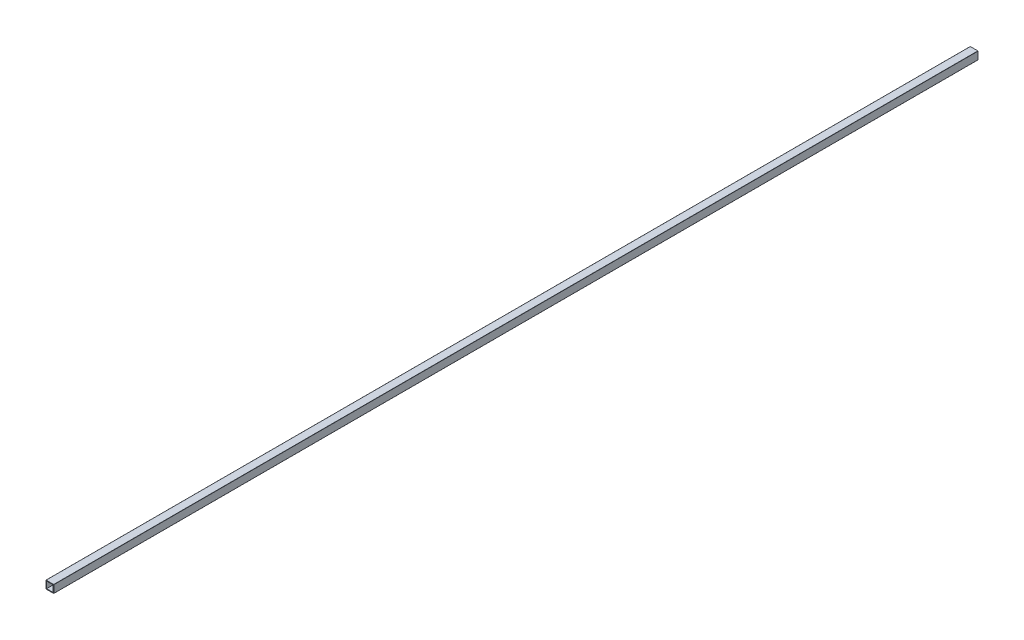
SolidWorks part; units mm, degrees
material "AISI 1035 Acero (SS)"
ref_plane "Alzado" through (0, 0, 0) normal (0, 0, 1) x (1, 0, 0)
ref_plane "Planta" through (0, 0, 0) normal (0, 1, 0) x (1, 0, 0)
ref_plane "Vista lateral" through (0, 0, 0) normal (1, 0, 0) x (0, 0, -1)
sketch "Croquis1" plane through (0, 0, 0) normal (0, 0, 1) x (1, 0, 0)
  line L0 (-21.6, -21.6) -> (-21.6, 21.6)
  line L1 (-24.4, -25.4) -> (24.4, -25.4)
  line L2 (-25.4, -24.4) -> (-25.4, 24.4)
  line L3 (-24.4, 25.4) -> (24.4, 25.4)
  line L4 (25.4, -24.4) -> (25.4, 24.4)
  line L5 (-25.4, -25.4) -> (25.4, 25.4) construction
  line L6 (-25.4, 25.4) -> (25.4, -25.4) construction
  line L7 (-21.6, 21.6) -> (21.6, 21.6)
  line L8 (21.6, -21.6) -> (21.6, 21.6)
  line L9 (-21.6, -21.6) -> (21.6, -21.6)
  line L10 (-25.4, 25.4) -> (25.4, 25.4) construction
  line L11 (25.4, -25.4) -> (25.4, 25.4) construction
  line L12 (-25.4, -25.4) -> (25.4, -25.4) construction
  line L13 (-25.4, -25.4) -> (-25.4, 25.4) construction
  arc A0 (24.4, 25.4) -> (25.4, 24.4) centre (24.4, 24.4) cw
  arc A1 (24.4, -25.4) -> (25.4, -24.4) centre (24.4, -24.4) ccw
  arc A2 (-24.4, -25.4) -> (-25.4, -24.4) centre (-24.4, -24.4) cw
  arc A3 (-25.4, 24.4) -> (-24.4, 25.4) centre (-24.4, 24.4) cw
  point P0 (0, 0)
  dimension "D2" = 1
  dimension "D1" = 50.8
  dimension "D3" = 3.8
extrude "Saliente-Extruir1" add sketch "Croquis1" along normal blind 6000
